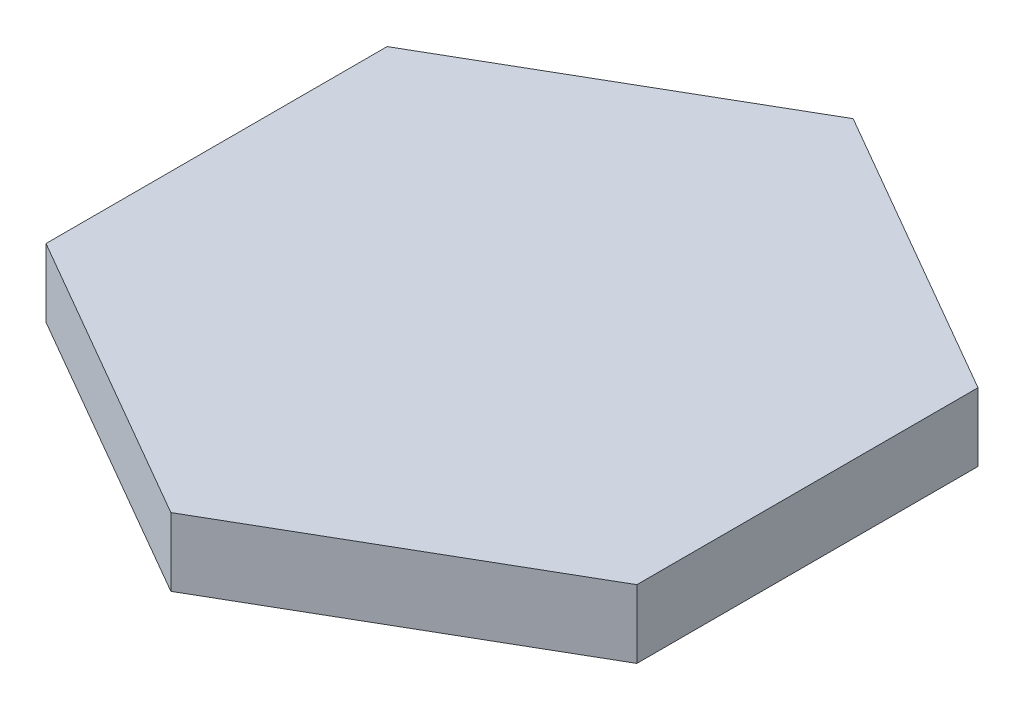
SolidWorks part; units mm, degrees
ref_plane "Front Plane" through (0, 0, 0) normal (0, 0, 1) x (1, 0, 0)
ref_plane "Top Plane" through (0, 0, 0) normal (0, 1, 0) x (1, 0, 0)
ref_plane "Right Plane" through (0, 0, 0) normal (1, 0, 0) x (0, 0, -1)
sketch "Sketch1" plane through (0, 0, 0) normal (0, 1, 0) x (1, 0, 0)
  line L1 (27.4963, 15.875) -> (0, 31.75)
  line L2 (0, 31.75) -> (-27.4963, 15.875)
  line L3 (-27.4963, 15.875) -> (-27.4963, -15.875)
  line L4 (-27.4963, -15.875) -> (0, -31.75)
  line L5 (0, -31.75) -> (27.4963, -15.875)
  line L6 (27.4963, -15.875) -> (27.4963, 15.875)
  line L7 (21.8831, 12.8954) -> (-0.2262, 25.399)
  line L8 (-0.2262, 25.399) -> (-22.1093, 12.5036)
  line L9 (-22.1093, 12.5036) -> (-21.8831, -12.8954)
  line L10 (-21.8831, -12.8954) -> (0.2262, -25.399)
  line L11 (0.2262, -25.399) -> (22.1093, -12.5036)
  line L12 (22.1093, -12.5036) -> (21.8831, 12.8954)
  circle A0 centre (0, 0) radius 27.4963 construction
  circle A1 centre (0, 0) radius 21.997 construction
  point P1 (0, 0)
  point P17 (0, 0)
  dimension "D1" = 31.75
  dimension "D2" = 25.4
  dimension "D3" = 25.399
  dimension "D4" = 6.355
extrude "Boss-Extrude1" add sketch "Sketch1" against normal blind 6.35 contours L1 L2 L3 L4 L5 L6
